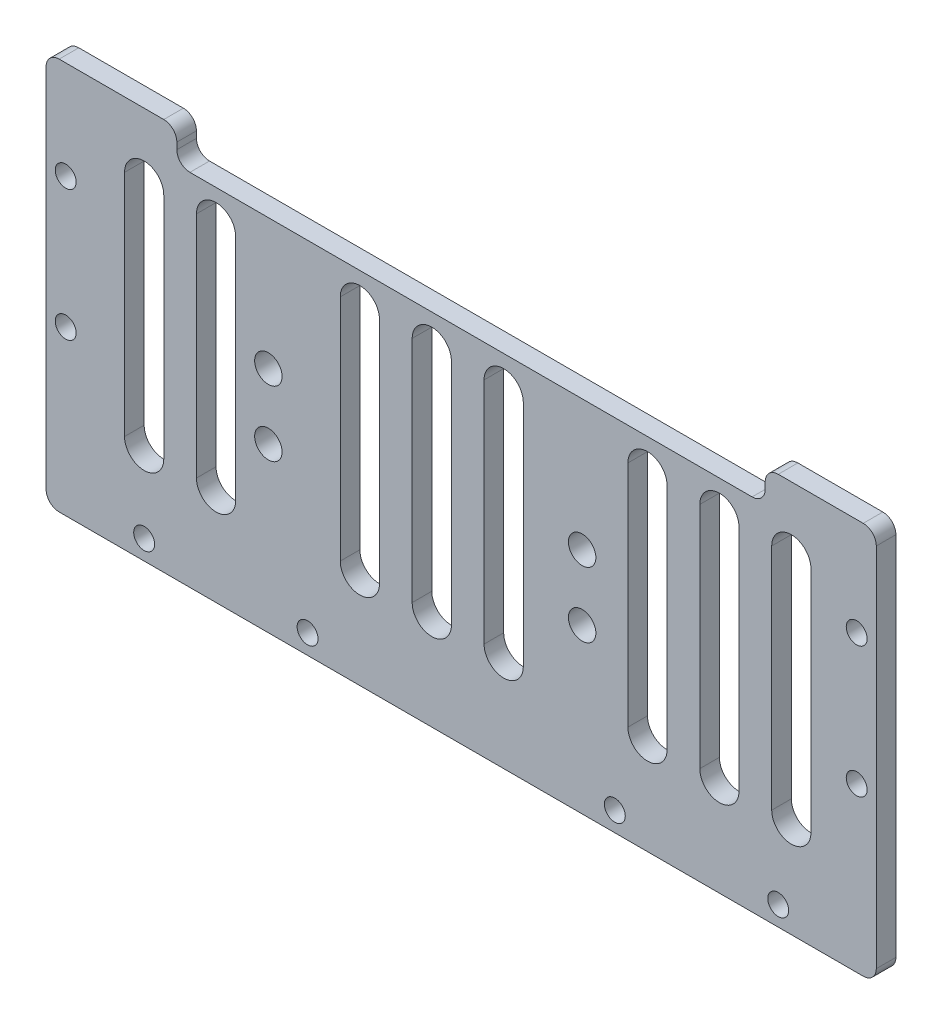
SolidWorks part; units mm, degrees
ref_plane "前视基准面" through (0, 0, 0) normal (0, 0, 1) x (1, 0, 0)
ref_plane "上视基准面" through (0, 0, 0) normal (0, 1, 0) x (1, 0, 0)
ref_plane "右视基准面" through (0, 0, 0) normal (1, 0, 0) x (0, 0, -1)
other "Configuration Table"
sketch "草图1" plane through (0, 0, 0) normal (0, 0, 1) x (1, 0, 0)
  line L1 (2, 0) -> (125, 0)
  line L2 (0, 2) -> (0, 58)
  line L3 (2, 60) -> (125, 60)
  line L4 (127, 2) -> (127, 58)
  arc A0 (125, 0) -> (127, 2) centre (125, 2) ccw
  arc A1 (0, 2) -> (2, 0) centre (2, 2) ccw
  arc A2 (125, 60) -> (127, 58) centre (125, 58) cw
  arc A3 (0, 58) -> (2, 60) centre (2, 58) cw
  point P7 (127, 0)
  point P10 (0, 0)
  point P13 (127, 60)
  dimension "D3" = 2
  dimension "D1" = 127
  dimension "D2" = 60
extrude "凸台-拉伸1" add sketch "草图1" along normal blind 3
sketch "草图2" plane through (0, 0, 3) normal (0, 0, 1) x (1, 0, 0)
  line L0 (0, 3) -> (127, 3) construction
  line L1 (0, 58) -> (0, 2) construction
  line L2 (127, 2) -> (127, 58) construction
  line L3 (2, 0) -> (125, 0) construction
  circle A0 centre (15, 3) radius 1.6
  circle A1 centre (40, 3) radius 1.6
  circle A2 centre (87, 3) radius 1.6
  circle A3 centre (112, 3) radius 1.6
  dimension "D2" = 3.2
  dimension "D4" = 25
  dimension "D5" = 47
  dimension "D6" = 25
  dimension "D1" = 3
  dimension "D3" = 15
extrude "切除-拉伸1" cut sketch "草图2" against normal up to next
sketch "草图3" plane through (0, 0, 3) normal (0, 0, 1) x (1, 0, 0)
  line L0 (3, 60) -> (3, 0) construction
  line L1 (125, 60) -> (2, 60) construction
  line L2 (2, 0) -> (125, 0) construction
  line L3 (0, 58) -> (0, 2) construction
  line L4 (63.5, 75.938) -> (63.5, -10.4733) construction
  line L5 (127, 2) -> (127, 58) construction
  circle A0 centre (3, 45) radius 1.6
  circle A1 centre (3, 25) radius 1.6
  circle A2 centre (124, 25) radius 1.6
  circle A3 centre (124, 45) radius 1.6
  dimension "D2" = 3.2
  dimension "D3" = 15
  dimension "D4" = 20
  dimension "D5" = 3
  dimension "D1" = 3
extrude "切除-拉伸2" cut sketch "草图3" against normal blind 3
sketch "草图4" plane through (0, 0, 3) normal (0, 0, 1) x (1, 0, 0)
  line L0 (0, 58) -> (0, 2) construction
  line L1 (82, 25) -> (34, 25) construction
  line L2 (82, 25) -> (82, 35) construction
  line L3 (82, 35) -> (34, 35) construction
  line L4 (34, 25) -> (34, 35) construction
  line L6 (125, 60) -> (2, 60) construction
  circle A0 centre (82, 35) radius 2.1
  circle A1 centre (34, 35) radius 2.1
  circle A2 centre (34, 25) radius 2.1
  circle A3 centre (82, 25) radius 2.1
  dimension "D5" = 4.2
  dimension "D1" = 10
  dimension "D2" = 48
  dimension "D3" = 34
  dimension "D4" = 25
extrude "切除-拉伸3" cut sketch "草图4" against normal blind 10
sketch "草图5" plane through (0, 0, 0) normal (0, 0, -1) x (-1, 0, 0)
  line L0 (-114, 50) -> (-114, 15) construction
  line L1 (-111, 50) -> (-111, 15)
  line L2 (-117, 50) -> (-117, 15)
  line L3 (-2, 0) -> (-125, 0) construction
  line L4 (-127, 2) -> (-127, 58) construction
  line L5 (-103, 50) -> (-103, 15) construction
  line L6 (-100, 50) -> (-100, 15)
  line L7 (-106, 50) -> (-106, 15)
  line L8 (-92, 50) -> (-92, 15) construction
  line L9 (-89, 50) -> (-89, 15)
  line L10 (-95, 50) -> (-95, 15)
  line L14 (-70, 50) -> (-70, 15) construction
  line L15 (-67, 50) -> (-67, 15)
  line L16 (-73, 50) -> (-73, 15)
  line L17 (-59, 50) -> (-59, 15) construction
  line L18 (-56, 50) -> (-56, 15)
  line L19 (-62, 50) -> (-62, 15)
  line L20 (-48, 50) -> (-48, 15) construction
  line L21 (-45, 50) -> (-45, 15)
  line L22 (-51, 50) -> (-51, 15)
  line L26 (-26, 50) -> (-26, 15) construction
  line L27 (-23, 50) -> (-23, 15)
  line L28 (-29, 50) -> (-29, 15)
  line L29 (-15, 50) -> (-15, 15) construction
  line L30 (-12, 50) -> (-12, 15)
  line L31 (-18, 50) -> (-18, 15)
  line L49 (-37, 50) -> (-37, 15) construction
  line L50 (-34, 50) -> (-34, 15)
  line L51 (-40, 50) -> (-40, 15)
  line L52 (-81, 50) -> (-81, 15) construction
  line L53 (-78, 50) -> (-78, 15)
  line L54 (-84, 50) -> (-84, 15)
  line L55 (-37, 50) -> (-37, 15) construction
  line L56 (-34, 50) -> (-34, 15)
  line L57 (-40, 50) -> (-40, 15)
  line L58 (-81, 50) -> (-81, 15) construction
  line L59 (-78, 50) -> (-78, 15)
  line L60 (-84, 50) -> (-84, 15)
  arc A0 (-111, 50) -> (-117, 50) centre (-114, 50) ccw
  arc A1 (-117, 15) -> (-111, 15) centre (-114, 15) ccw
  arc A2 (-100, 50) -> (-106, 50) centre (-103, 50) ccw
  arc A3 (-106, 15) -> (-100, 15) centre (-103, 15) ccw
  arc A4 (-89, 50) -> (-95, 50) centre (-92, 50) ccw
  arc A5 (-95, 15) -> (-89, 15) centre (-92, 15) ccw
  arc A8 (-67, 50) -> (-73, 50) centre (-70, 50) ccw
  arc A9 (-73, 15) -> (-67, 15) centre (-70, 15) ccw
  arc A10 (-56, 50) -> (-62, 50) centre (-59, 50) ccw
  arc A11 (-62, 15) -> (-56, 15) centre (-59, 15) ccw
  arc A12 (-45, 50) -> (-51, 50) centre (-48, 50) ccw
  arc A13 (-51, 15) -> (-45, 15) centre (-48, 15) ccw
  arc A16 (-23, 50) -> (-29, 50) centre (-26, 50) ccw
  arc A17 (-29, 15) -> (-23, 15) centre (-26, 15) ccw
  arc A18 (-12, 50) -> (-18, 50) centre (-15, 50) ccw
  arc A19 (-18, 15) -> (-12, 15) centre (-15, 15) ccw
  arc A36 (-34, 50) -> (-40, 50) centre (-37, 50) ccw
  arc A37 (-40, 15) -> (-34, 15) centre (-37, 15) ccw
  arc A38 (-78, 50) -> (-84, 50) centre (-81, 50) ccw
  arc A39 (-84, 15) -> (-78, 15) centre (-81, 15) ccw
  point P2 (-114, 32.5)
  point P14 (-103, 32.5)
  point P21 (-92, 32.5)
  point P27 (-37, 32.5)
  point P34 (-70, 32.5)
  point P41 (-59, 32.5)
  point P48 (-48, 32.5)
  point P62 (-26, 32.5)
  point P69 (-15, 32.5)
  point P76 (-81, 32.5)
  point P83 (-37, 32.5)
  point P90 (-81, 32.5)
  point P97 (-37, 32.5)
  point P104 (-81, 32.5)
  point P111 (-37, 32.5)
  point P118 (-81, 32.5)
  point P125 (-37, 32.5)
  point P132 (-81, 32.5)
  dimension "D1" = 3
  dimension "D3" = 15
  dimension "D2" = 35
  dimension "D4" = 10
  dimension "D6" = 5
  dimension "D5" = 10
extrude "切除-拉伸4" cut sketch "草图5" against normal blind 10
sketch "草图6" plane through (0, 0, 0) normal (0, 0, -1) x (-1, 0, 0)
  line L0 (-125, 60) -> (-2, 60) construction
  line L1 (-110, 60) -> (-20, 60)
  line L2 (-110, 60) -> (-110, 55)
  line L3 (-110, 55) -> (-20, 55)
  line L4 (-20, 60) -> (-20, 55)
  line L5 (0, 58) -> (0, 2) construction
  dimension "D1" = 90
  dimension "D2" = 20
  dimension "D3" = 5
extrude "切除-拉伸5" cut sketch "草图6" against normal blind 10
fillet "圆角1" radius 2 4 edges at (20, 60, 1.5) (20, 55, 1.5) (110, 55, 1.5) (110, 60, 1.5)
